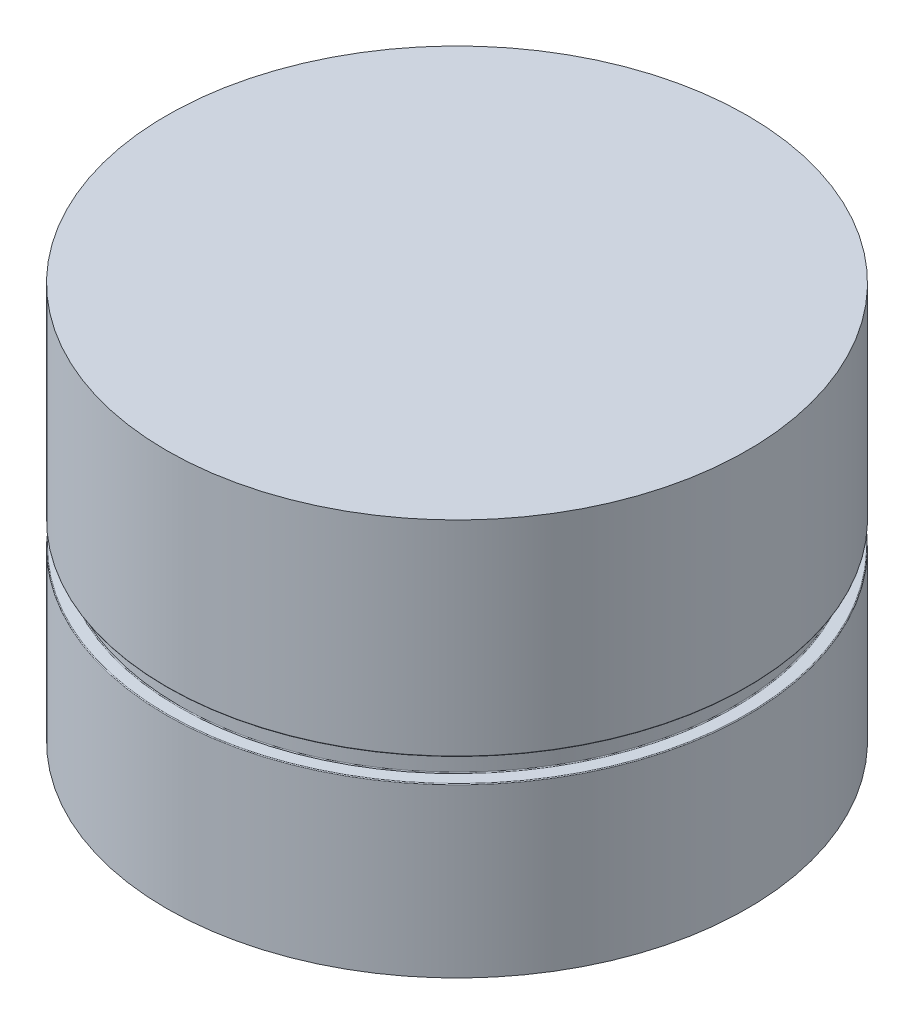
SolidWorks part; units mm, degrees
ref_plane "Front Plane" through (0, 0, 0) normal (0, 0, 1) x (1, 0, 0)
ref_plane "Top Plane" through (0, 0, 0) normal (0, 1, 0) x (1, 0, 0)
ref_plane "Right Plane" through (0, 0, 0) normal (1, 0, 0) x (0, 0, -1)
sketch "Sketch1" plane through (0, 0, 0) normal (0, 0, 1) x (1, 0, 0)
  line L0 (0, 32.1894) -> (0, -38.988) construction
  line L1 (0, -33.4044) -> (-46.4693, -33.4044)
  line L2 (-46.4693, -33.4044) -> (-46.4693, -6.5207)
  line L3 (-46.4693, -6.5207) -> (-44.4373, -6.4142)
  line L4 (-44.4373, -6.4142) -> (-44.4373, -2.8582)
  line L5 (-44.4373, -2.8582) -> (-46.4693, -2.7517)
  line L6 (-46.4693, -2.7517) -> (-46.4693, 30.0956)
  line L7 (-46.4693, 30.0956) -> (0, 30.0956)
  line L8 (0, 30.0956) -> (0, -33.4044)
  dimension "D1" = 92.9386
  dimension "D2" = 92.9386
  dimension "D3" = 88.8746
  dimension "D4" = 93
  dimension "D5" = 93
  dimension "D6" = 3.556
  dimension "D7" = 63.5
revolve "Revolve3" add sketch "Sketch1" angle 360 about L0
fillet "Fillet1" radius 0.127 2 edges at (0, -6.5207, 46.4693) (0, -2.7517, 46.4693)
fillet "Fillet2" radius 0.127 2 edges at (0, -2.8582, 44.4373) (0, -6.4142, 44.4373)
